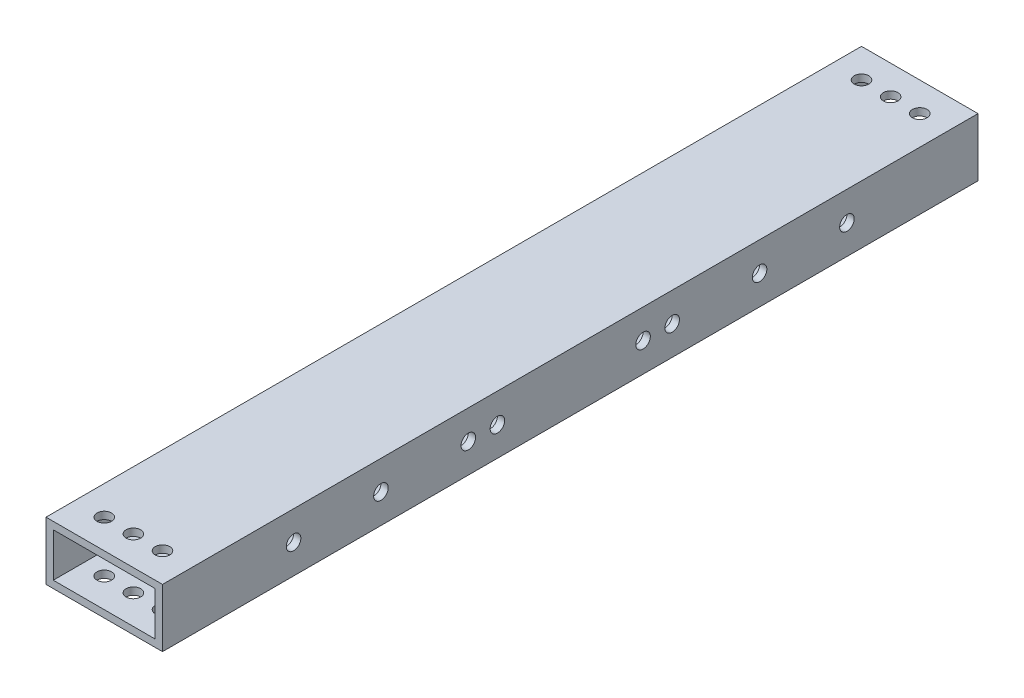
SolidWorks part; units mm, degrees
ref_plane "Front Plane" through (0, 0, 0) normal (0, 0, 1) x (1, 0, 0)
ref_plane "Top Plane" through (0, 0, 0) normal (0, 1, 0) x (1, 0, 0)
ref_plane "Right Plane" through (0, 0, 0) normal (1, 0, 0) x (0, 0, -1)
sketch "Sketch1" plane through (0, 0, 0) normal (0, 0, 1) x (1, 0, 0)
  line L0 (3.175, 22.225) -> (47.625, 22.225)
  line L1 (0, 0) -> (50.8, 0)
  line L2 (0, 0) -> (0, 25.4)
  line L3 (0, 25.4) -> (50.8, 25.4)
  line L4 (50.8, 0) -> (50.8, 25.4)
  line L5 (47.625, 3.175) -> (47.625, 22.225)
  line L6 (3.175, 3.175) -> (47.625, 3.175)
  line L7 (3.175, 3.175) -> (3.175, 22.225)
  dimension "D1" = 25.4
  dimension "D2" = 50.8
  dimension "D3" = 3.175
extrude "Boss-Extrude1" add sketch "Sketch1" along normal blind 355.6
sketch "Sketch2" plane through (0, 0, 0) normal (-1, 0, 0) x (0, 0, 1)
  line L0 (177.8, 25.4) -> (177.8, 12.7) construction
  line L1 (355.6, 25.4) -> (0, 25.4) construction
  line L2 (133.35, 12.7) -> (95.25, 12.7) construction
  line L4 (95.25, 12.7) -> (57.15, 12.7) construction
  line L5 (177.8, 12.7) -> (146.05, 12.7) construction
  line L6 (146.05, 12.7) -> (133.35, 12.7) construction
  circle A0 centre (133.35, 12.7) radius 3.175
  circle A1 centre (146.05, 12.7) radius 3.175
  circle A4 centre (95.25, 12.7) radius 3.175
  circle A5 centre (57.15, 12.7) radius 3.175
  circle A6 centre (209.55, 12.7) radius 3.175
  circle A7 centre (222.25, 12.7) radius 3.175
  circle A8 centre (260.35, 12.7) radius 3.175
  circle A9 centre (298.45, 12.7) radius 3.175
  dimension "D4" = 6.35
  dimension "D1" = 12.7
  dimension "D2" = 31.75
  dimension "D3" = 12.7
  dimension "D5" = 38.1
  dimension "D6" = 82.55
extrude "Cut-Extrude1" cut sketch "Sketch2" against normal through all both and the other way through all
hole_wizard "1/4 (0.25) Diameter Hole1" positions "Sketch3" profile "Sketch4" hole size "1/4" standard "ANSI Inch" end condition through all
sketch "Sketch3" plane through (0, 25.4, 0) normal (0, 1, 0) x (1, 0, 0)
  line L0 (12.7, -342.9) -> (25.4, -342.9)
  line L1 (25.4, -342.9) -> (38.1, -342.9)
  line L4 (25.4, -12.7) -> (12.7, -12.7)
  line L5 (12.7, -12.7) -> (12.7, -342.9)
  line L8 (0, -355.6) -> (0, 0) construction
  line L9 (25.4, -12.7) -> (38.1, -12.7)
  line L10 (50.8, 0) -> (0, 0) construction
  line L11 (50.8, -355.6) -> (0, -355.6) construction
  point P0 (12.7, -12.7)
  point P2 (25.4, -12.7)
  point P4 (38.1, -12.7)
  point P6 (12.7, -342.9)
  point P8 (25.4, -342.9)
  point P10 (38.1, -342.9)
  dimension "D2" = 12.7
  dimension "D1" = 12.7
  dimension "D3" = 12.7
  dimension "D4" = 12.7
  dimension "D5" = 12.7
  dimension "D6" = 12.7
  dimension "D7" = 12.7
sketch "Sketch4" plane through (12.7, 25.4, 12.7) normal (1, 0, 0) x (0, 0, 1)
  line L0 (0, 0) -> (0, 25.4)
  line L1 (0, 25.4) -> (3.175, 25.4)
  line L2 (3.175, 25.4) -> (3.175, 0)
  line L5 (3.175, 0) -> (0, 0)
  line L11 (0, -6.35) -> (0, 107.95) construction
  dimension "Thru Hole Dia." = 6.35
  dimension "Thru Hole Depth" = 25.4
